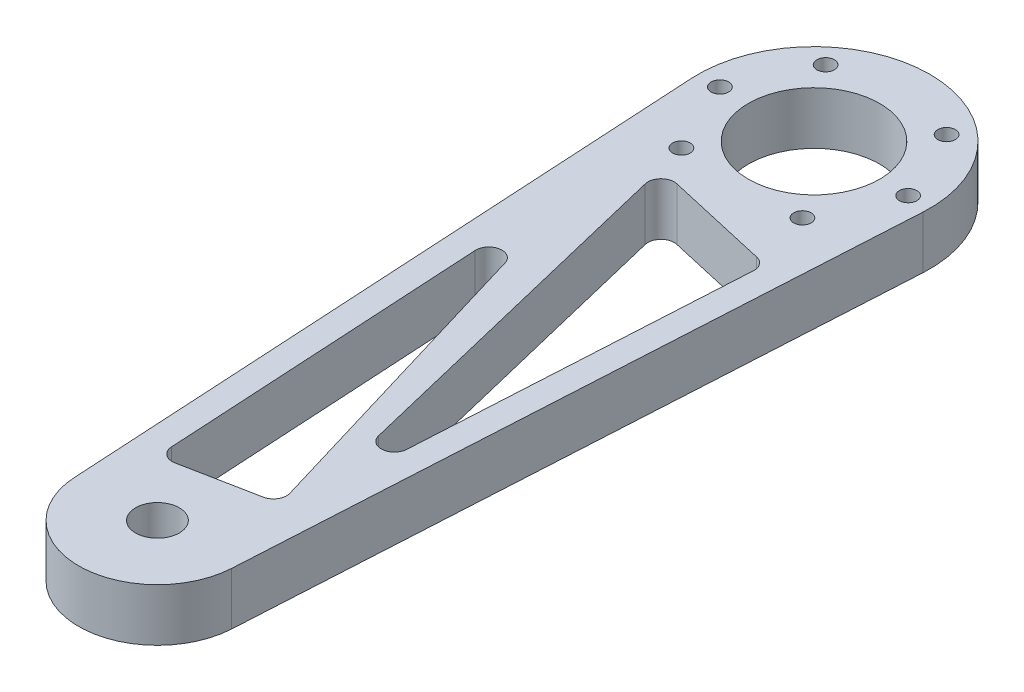
SolidWorks part; units mm, degrees
material "1060 合金"
ref_plane "前视基准面" through (0, 0, 0) normal (0, 0, 1) x (1, 0, 0)
ref_plane "上视基准面" through (0, 0, 0) normal (0, 1, 0) x (1, 0, 0)
ref_plane "右视基准面" through (0, 0, 0) normal (1, 0, 0) x (0, 0, -1)
sketch "草图1" plane through (0, 0, 0) normal (0, 1, 0) x (1, 0, 0)
  line L0 (0, 0) -> (0, 150) construction
  line L1 (-17.9711, -1.02) -> (-26.4574, 148.4983)
  line L2 (17.9711, -1.02) -> (26.4574, 148.4983)
  line L3 (-11.9807, -0.68) -> (-20.4671, 148.8383) construction
  line L4 (11.9807, -0.68) -> (20.4671, 148.8383) construction
  line L5 (-12.741, 12.7148) -> (13.0288, 17.7851) construction
  line L6 (13.0288, 17.7851) -> (18.8303, 120) construction
  line L7 (18.8303, 120) -> (-19.3219, 128.6624) construction
  line L8 (-19.3219, 128.6624) -> (-12.741, 12.7148) construction
  line L9 (13.0288, 17.7851) -> (-19.3219, 128.6624) construction
  line L10 (14.4687, 18.2052) -> (-17.882, 129.0826) construction
  line L12 (-12.741, 12.7148) -> (-18.5544, 115.1395)
  line L13 (-18.5544, 115.1395) -> (10.7129, 17.3294)
  line L14 (10.7129, 17.3294) -> (-12.741, 12.7148)
  line L15 (13.2832, 22.2683) -> (18.8303, 120)
  line L16 (-17.882, 129.0826) -> (-17.7319, 128.5683) construction
  line L17 (18.8303, 120) -> (-12, 127)
  line L18 (-12, 127) -> (13.2832, 22.2683)
  circle A0 centre (0, 150) radius 26.5 construction
  circle A1 centre (0, 0) radius 18 construction
  circle A2 centre (0, 0) radius 5
  circle A3 centre (0, 150) radius 15
  arc A4 (-17.9711, -1.02) -> (17.9711, -1.02) centre (0, 0) ccw
  arc A5 (-26.4574, 148.4983) -> (26.4574, 148.4983) centre (0, 150) cw
  arc A6 (-20.4671, 148.8383) -> (20.4671, 148.8383) centre (0, 150) cw construction
  arc A7 (-11.9807, -0.68) -> (11.9807, -0.68) centre (0, 0) ccw construction
  dimension "D2" = 53
  dimension "D3" = 36
  dimension "D4" = 10
  dimension "D5" = 30
  dimension "D1" = 150
  dimension "D9" = 30
  dimension "D10" = 23
  dimension "D11" = 12
  dimension "D6" = 6
  dimension "D7" = 1.5
extrude "凸台-拉伸1" add sketch "草图1" along normal blind 12
fillet "圆角1" radius 3 6 edges at (18.8303, 6, -120) (-12, 6, -127) (-18.5544, 6, -115.1395) (-12.741, 6, -12.7148) (13.2832, 6, -22.2683) (10.7129, 6, -17.3294)
sketch "草图2" plane through (0, 12, 0) normal (0, 1, 0) x (1, 0, 0)
  line L0 (0, 150) -> (-21.5, 150) construction
  line L1 (0, 150) -> (21.5, 150) construction
  circle A0 centre (-21.5, 150) radius 2
  circle A1 centre (21.5, 150) radius 2
  dimension "D2" = 4
  dimension "D1" = 21.5
extrude "切除-拉伸1" cut sketch "草图2" against normal through all
pattern_circular "阵列(圆周)1" [suppressed] count 3 over 360
sketch "草图3" plane through (0, 12, 0) normal (0, 1, 0) x (1, 0, 0)
  line L0 (0, 150) -> (14.25, 150) construction
  circle A0 centre (14.25, 150) radius 2
  dimension "D2" = 4
  dimension "D1" = 14.25
extrude "切除-拉伸2" [suppressed] cut sketch "草图3" against normal through all
pattern_circular "阵列(圆周)2" [suppressed] count 3 over 360
pattern_circular "阵列(圆周)3" count 2 every 50 about axis through (0, 0, -150) along (0, 1, 0) of "切除-拉伸1"
pattern_circular "阵列(圆周)4" count 2 every 50 about axis through (0, 0, -150) along (0, 1, 0) of "切除-拉伸1"
